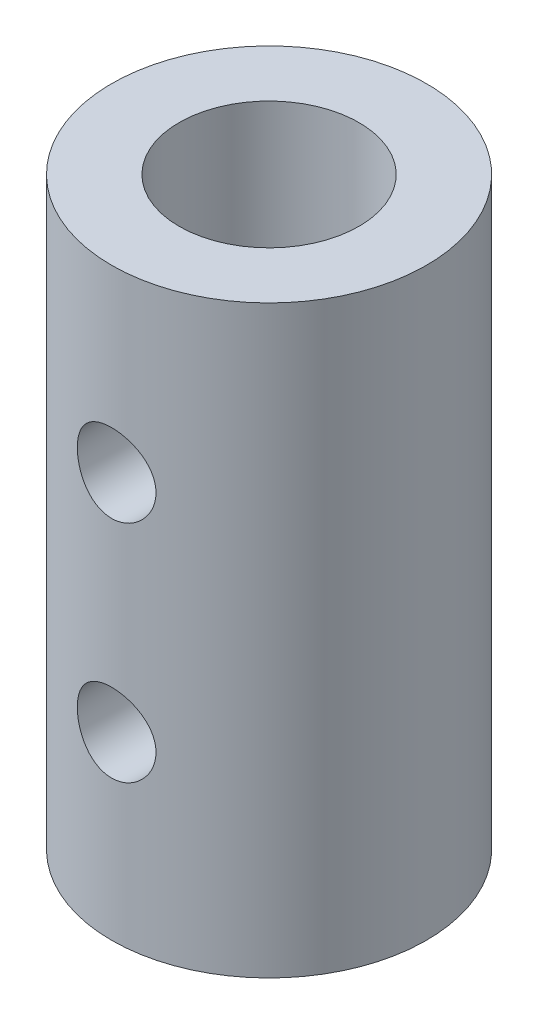
SolidWorks part; units mm, degrees
ref_plane "Plan de face" through (0, 0, 0) normal (0, 0, 1) x (1, 0, 0)
ref_plane "Plan de dessus" through (0, 0, 0) normal (0, 1, 0) x (1, 0, 0)
ref_plane "Plan de droite" through (0, 0, 0) normal (1, 0, 0) x (0, 0, -1)
sketch "Esquisse1" plane through (0, 0, 0) normal (0, 1, 0) x (1, 0, 0)
  circle A0 centre (0, 0) radius 20
  circle A1 centre (0, 0) radius 35
  dimension "D1" = 40
  dimension "D2" = 70
extrude "Boss.-Extru.1" add sketch "Esquisse1" along normal blind 130
sketch "Esquisse2" plane through (0, 0, 0) normal (0, 0, 1) x (1, 0, 0)
  line L0 (0, 130) -> (0, 90) construction
  line L1 (35, 130) -> (-35, 130) construction
  line L2 (0, 0) -> (0, 40) construction
  line L3 (-35, 0) -> (35, 0) construction
  circle A2 centre (0, 90) radius 8.75
  circle A3 centre (0, 40) radius 8.75
  dimension "D1" = 17.5
  dimension "D2" = 17.5
  dimension "D3" = 40
  dimension "D4" = 40
extrude "Enlèv. mat.-Extru.1" cut sketch "Esquisse2" against normal through all both and the other way through all
sketch "Esquisse4" plane through (0, 0, 0) normal (1, 0, 0) x (0, 0, -1)
  line L0 (0, 0) -> (0, 130) construction
  line L1 (35, 130) -> (-35, 130) construction
  circle A0 centre (0, 65) radius 7.5
  dimension "D1" = 15
extrude "Enlèv. mat.-Extru.2" cut sketch "Esquisse4" against normal through all
